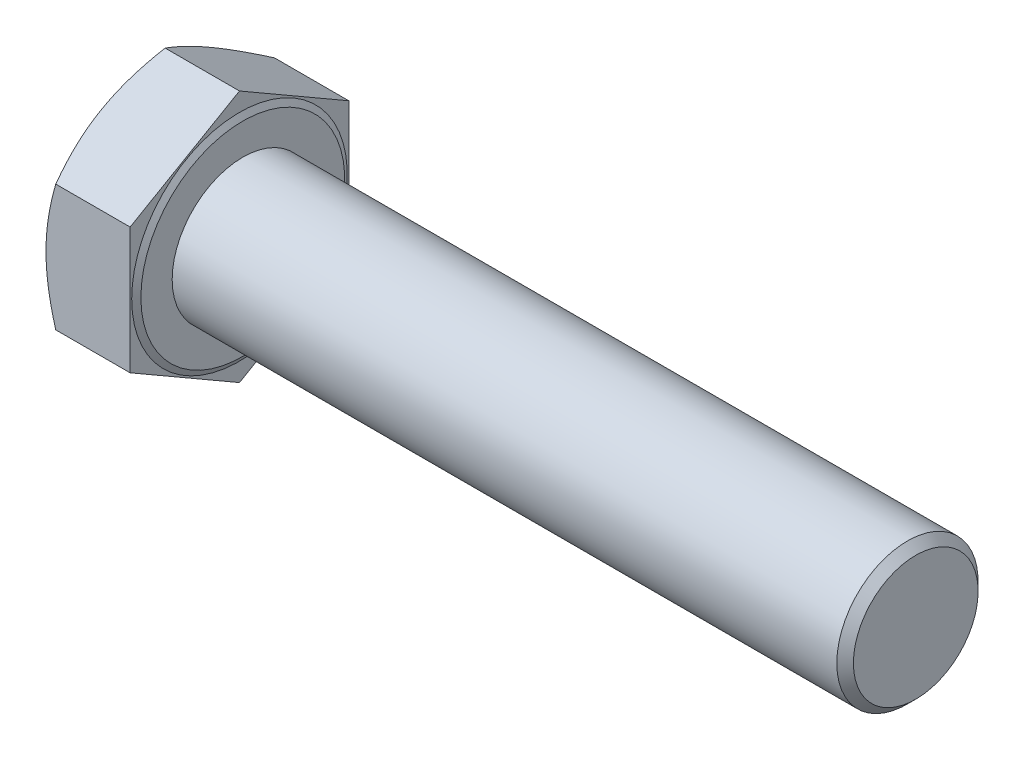
SolidWorks part; units mm, degrees
extrude "BaseHead" add sketch "HeadSke" along normal blind 26
sketch "HeadSke" plane through (0, 0, 0) normal (1, 0, 0) x (0, 0, -1)
  line L0 (32.5, 18.7639) -> (32.5, -18.7639)
  line L1 (-32.5, 18.7639) -> (-32.5, -18.7639)
  line L2 (32.5, -18.7639) -> (0, -37.5278)
  line L3 (0, -37.5278) -> (-32.5, -18.7639)
  line L4 (32.5, 18.7639) -> (0, 37.5278)
  line L5 (0, 37.5278) -> (-32.5, 18.7639)
  line L6 (0, 37.5278) -> (0, -37.5278) construction
  dimension "Width_flats" = 65
  dimension "D2" = 120
ref_plane "Plane1" through (0, 0, 0) normal (0, 0, 1) x (1, 0, 0)
ref_plane "Plane2" through (0, 0, 0) normal (0, 1, 0) x (1, 0, 0)
ref_plane "Plane3" through (0, 0, 0) normal (1, 0, 0) x (0, 0, -1)
sketch "BodySke" plane through (0, 0, 0) normal (0, 0, 1) x (1, 0, 0)
  line L0 (0, 18.7639) -> (0, -18.7639) construction
  line L1 (0, 0) -> (226, 0)
  line L2 (0, 0) -> (0, 21)
  line L3 (0, 21) -> (223.533, 21)
  line L4 (226, 0) -> (226, 18.533)
  line L5 (26, 37.5278) -> (26, 18.7639) construction
  line L6 (226, 18.533) -> (223.533, 21)
  line L7 (0, 0) -> (96.52, 0) construction
  line L8 (226, -18.533) -> (223.533, -21) construction
  line L9 (0, -21) -> (223.533, -21) construction
  line L10 (30.5, 15.24) -> (30.5, -1.27) construction
  line L11 (181, 15.24) -> (181, -13.0561) construction
  line L12 (26, 18.7639) -> (26, -18.7639) construction
  dimension "Thread_nom" = 45
  dimension "Diameter" = 42
  dimension "Advance" = 4.5
revolve "BaseBody" add sketch "BodySke"
cosmetic thread "ThreadCosmetic" [suppressed]
fillet "HeadFillet" [suppressed] radius 1.2
sketch "Sketch3" plane through (0, 0, 0) normal (0, 1, 0) x (1, 0, 0)
  line L0 (-8.125, 18.4271) -> (8.125, 46.5729)
  line L1 (0, 0) -> (0, -32.5) construction
  line L2 (0, 32.5) -> (0, 0) construction
  line L3 (-8.125, 18.4271) -> (-29.7756, 30.9271)
  line L4 (-29.7756, 30.9271) -> (-13.5256, 59.0729)
  line L5 (-13.5256, 59.0729) -> (8.125, 46.5729)
  line L6 (0, 0) -> (99.06, 0) construction
  point P11 (0, 32.5)
  dimension "D1" = 25
  dimension "Head_ch_ang" = 30
revolve "HeadChamfer" cut sketch "Sketch3" angle 360 about L6
sketch "BearingSke" plane through (0, 0, 0) normal (0, 0, 1) x (1, 0, 0)
  line L0 (26, 37.5278) -> (2.9028, 37.5278) construction
  line L1 (26, 37.5278) -> (26, 18.7639) construction
  line L2 (26, 30.3) -> (25, 32.0321)
  line L3 (26, 30.3) -> (26, 37.5278)
  line L4 (26, 37.5278) -> (25, 37.5278)
  line L5 (0, 0) -> (95.25, 0) construction
  line L6 (0, 0) -> (96.52, 0) construction
  line L7 (25, 32.0321) -> (25, 37.5278)
  dimension "D1" = 30
  dimension "Bearing_ht" = 1
  dimension "Bearing_dia" = 60.6
revolve "BearingFace" cut sketch "BearingSke" angle 360 about L5
sketch "ThdSchSke" plane through (0, 0, 0) normal (0, 0, 1) x (1, 0, 0)
  line L0 (185.5, -18.533) -> (183.7726, -21)
  line L1 (185.5, -18.533) -> (187.2274, -21)
  line L2 (187.2274, -21) -> (187.2274, -26.25)
  line L3 (-3.175, 0) -> (5.1513, 0) construction
  line L5 (187.2274, -26.25) -> (183.7726, -26.25)
  line L6 (183.7726, -26.25) -> (183.7726, -21)
  dimension "Thread_minor" = 37.066
  dimension "Diameter" = 42
  dimension "Start" = 185.5
revolve "ThreadSchematic" [suppressed] cut sketch "ThdSchSke" angle 360 about L3
pattern_linear "ThdSchPat" [suppressed]
equation "\"Thread_minor@ThreadCosmetic\" = \"Minor_dia@BodySke\""
equation "\"Thread_length@ThreadCosmetic\" = \"Thread_nom@BodySke\" - \"Advance@BodySke\""
equation "\"Thread_minor@ThdSchSke\" = \"Minor_dia@BodySke\""
equation "\"Diameter@ThdSchSke\" = \"Diameter@BodySke\""
equation "\"Overcut@ThdSchSke\" = \"Diameter@BodySke\" * 1.25"
equation "\"Start@ThdSchSke\" = \"Head_ht@BaseHead\" + \"Length@BodySke\" - \"Thread_length@ThreadCosmetic\"  '---Non-countersunk---"
equation "\"Num_threads@ThdSchPat\" = int( \"Thread_length@ThreadCosmetic\" / \"Advance@BodySke\" + 0.999 )  + 1"
equation "\"Advance@ThdSchPat\" = \"Thread_length@ThreadCosmetic\" /  (\"Num_threads@ThdSchPat\" - 1) 'relax it"
equation "\"Num_threads@ThdSchPat\" = \"Num_threads@ThdSchPat\" - sgn( \"Num_threads@ThdSchPat\" - 1) '---chamfered tips only---"
